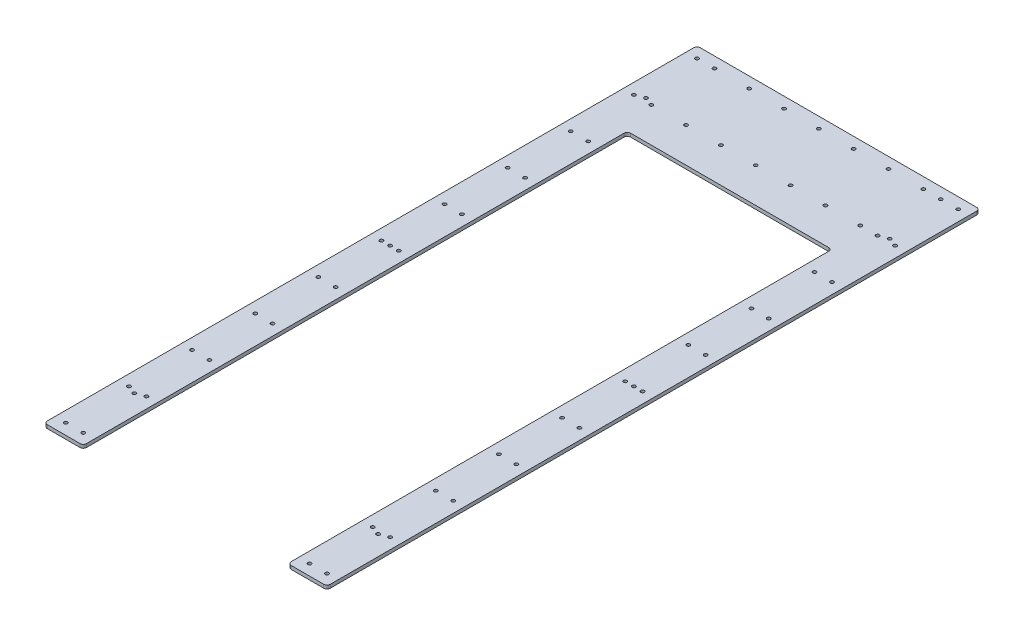
SolidWorks part; units mm, degrees
ref_plane "Front Plane" through (0, 0, 0) normal (0, 0, 1) x (1, 0, 0)
ref_plane "Top Plane" through (0, 0, 0) normal (0, 1, 0) x (1, 0, 0)
ref_plane "Right Plane" through (0, 0, 0) normal (1, 0, 0) x (0, 0, -1)
sketch "Sketch1" plane through (0, 0, 0) normal (0, 1, 0) x (1, 0, 0)
  line L0 (0, 300) -> (0, -300) construction
  line L1 (-130, -300) -> (-94, -300)
  line L2 (-130, -300) -> (-130, 300)
  line L3 (-130, 300) -> (130, 300)
  line L4 (130, -300) -> (130, 300)
  line L5 (-130, -300) -> (130, 300) construction
  line L6 (-130, 300) -> (130, -300) construction
  line L9 (-94, 200) -> (94, 200)
  line L11 (-94, 200) -> (-94, -300)
  line L12 (94, 200) -> (94, -300)
  line L13 (-130, 0) -> (130, 0) construction
  line L18 (94, -300) -> (130, -300)
  line L20 (112, -300) -> (112, 300) construction
  circle A0 centre (120, 290) radius 1.6
  circle A1 centre (120, 232) radius 1.6
  circle A2 centre (120, 174) radius 1.6
  circle A3 centre (120, 116) radius 1.6
  circle A4 centre (120, 58) radius 1.6
  circle A5 centre (120, 0) radius 1.6
  circle A6 centre (120, -58) radius 1.6
  circle A7 centre (120, -116) radius 1.6
  circle A8 centre (120, -174) radius 1.6
  circle A9 centre (120, -232) radius 1.6
  circle A10 centre (120, -290) radius 1.6
  circle A11 centre (-120, 232) radius 1.6
  circle A12 centre (-120, -290) radius 1.6
  circle A13 centre (-120, -232) radius 1.6
  circle A14 centre (-120, -174) radius 1.6
  circle A15 centre (-120, -116) radius 1.6
  circle A16 centre (-120, -58) radius 1.6
  circle A17 centre (-120, 0) radius 1.6
  circle A18 centre (-120, 58) radius 1.6
  circle A19 centre (-120, 116) radius 1.6
  circle A20 centre (-120, 174) radius 1.6
  circle A21 centre (-120, 290) radius 1.6
  circle A22 centre (112, 235) radius 1.6
  circle A23 centre (-112, 235) radius 1.6
  circle A24 centre (112, -235) radius 1.6
  circle A25 centre (-112, -235) radius 1.6
  circle A26 centre (104, 290) radius 1.6
  circle A27 centre (104, 232) radius 1.6
  circle A28 centre (104, 174) radius 1.6
  circle A29 centre (104, 116) radius 1.6
  circle A30 centre (104, 58) radius 1.6
  circle A31 centre (104, 0) radius 1.6
  circle A32 centre (104, -58) radius 1.6
  circle A33 centre (104, -116) radius 1.6
  circle A34 centre (104, -174) radius 1.6
  circle A35 centre (104, -232) radius 1.6
  circle A36 centre (104, -290) radius 1.6
  circle A37 centre (-104, -290) radius 1.6
  circle A38 centre (-104, -232) radius 1.6
  circle A39 centre (-104, -174) radius 1.6
  circle A40 centre (-104, -116) radius 1.6
  circle A41 centre (-104, -58) radius 1.6
  circle A42 centre (-104, 0) radius 1.6
  circle A43 centre (-104, 58) radius 1.6
  circle A44 centre (-104, 116) radius 1.6
  circle A45 centre (-104, 174) radius 1.6
  circle A46 centre (-104, 232) radius 1.6
  circle A47 centre (-104, 290) radius 1.6
  circle A49 centre (112, 0) radius 1.6
  circle A50 centre (-112, 0) radius 1.6
  circle A51 centre (-72, 290) radius 1.6
  circle A52 centre (-40, 290) radius 1.6
  circle A53 centre (-8, 290) radius 1.6
  circle A54 centre (24, 290) radius 1.6
  circle A55 centre (56, 290) radius 1.6
  circle A56 centre (88, 290) radius 1.6
  circle A58 centre (-72, 232) radius 1.6
  circle A59 centre (-40, 232) radius 1.6
  circle A60 centre (-8, 232) radius 1.6
  circle A61 centre (24, 232) radius 1.6
  circle A62 centre (56, 232) radius 1.6
  circle A63 centre (88, 232) radius 1.6
  circle A65 centre (120, 290) radius 1.6 [skipped]
  circle A66 centre (120, 232) radius 1.6 [skipped]
  point P0 (0, 0)
  point P6 (0, 0)
  dimension "D3" = 3.2
  dimension "D7" = 3.2
  dimension "D11" = 3.2
  dimension "D15" = 3.2
  dimension "D1" = 600
  dimension "D2" = 260
  dimension "D4" = 10
  dimension "D5" = 10
  dimension "D9" = 188
  dimension "D12" = 16
  dimension "D10" = 100
  dimension "D14" = 94
  dimension "D8" = 235
  dimension "D6" = 11
  dimension "D13" = 11
  dimension "D16" = 8
  dimension "D17" = 8
extrude "Boss-Extrude1" add sketch "Sketch1" along normal blind 3.175
fillet "Fillet1" radius 3 8 edges at (130, 1.5875, 300) (-130, 1.5875, 300) (130, 1.5875, -300) (-130, 1.5875, -300) (94, 1.5875, 300) (-94, 1.5875, 300) (94, 1.5875, -200) (-94, 1.5875, -200)
equation "\"width\"=260"
equation "\"length\"= 600"
equation "\"D2@Sketch1\"=\"width\""
equation "\"D1@Sketch1\"=\"length\""
equation "\"m3\"= 3.2"
